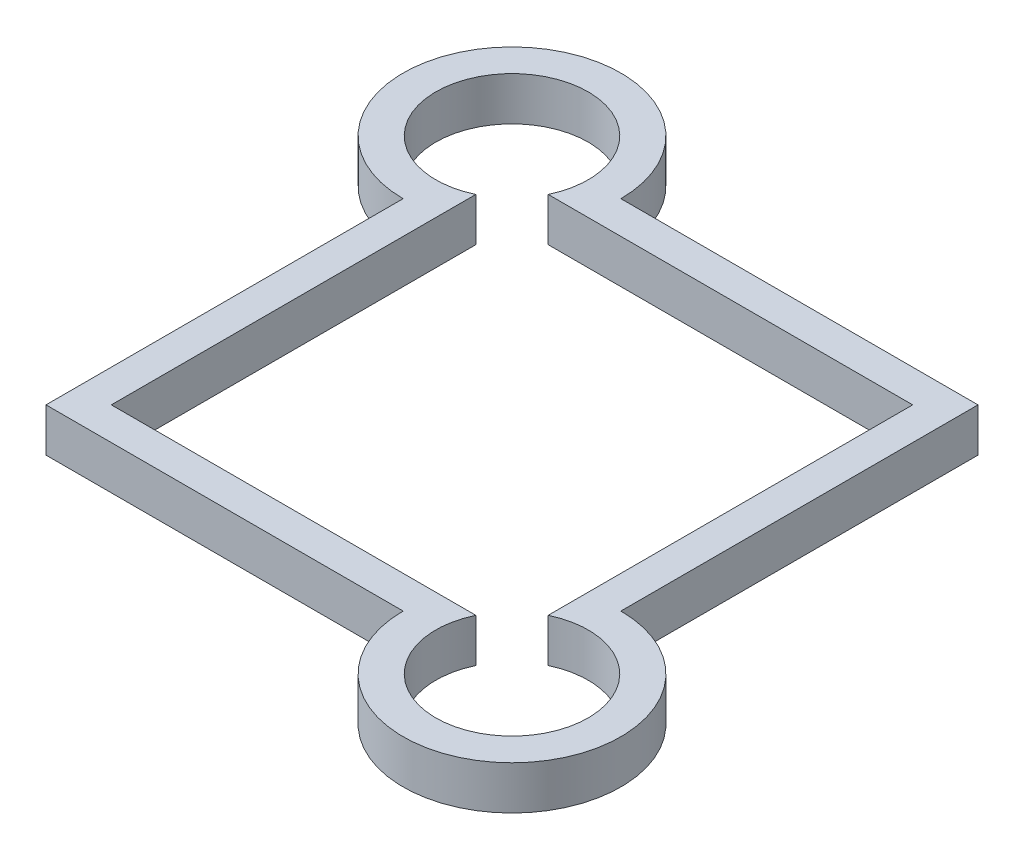
SolidWorks part; units mm, degrees
ref_plane "Ön Düzlem" through (0, 0, 0) normal (0, 0, 1) x (1, 0, 0)
ref_plane "Üst Düzlem" through (0, 0, 0) normal (0, 1, 0) x (1, 0, 0)
ref_plane "Sağ Düzlem" through (0, 0, 0) normal (1, 0, 0) x (0, 0, -1)
sketch "Çizim1" plane through (0, 0, 0) normal (0, 1, 0) x (1, 0, 0)
  line L0 (-66.2238, 67.3805) -> (101.1534, 67.3805)
  line L1 (-47.8466, 82.3805) -> (116.1534, 82.3805)
  line L2 (-97.8466, 32.3805) -> (-97.8466, -131.6195)
  line L3 (-97.8466, -131.6195) -> (66.1534, -131.6195)
  line L4 (116.1534, 82.3805) -> (116.1534, -81.6195)
  line L5 (-82.8466, 50.7578) -> (-82.8466, -116.6195)
  line L6 (-82.8466, -116.6195) -> (84.5306, -116.6195)
  line L7 (101.1534, 67.3805) -> (101.1534, -99.9967)
  line L8 (-97.8466, 117.3805) -> (-97.8466, 123.0819) construction
  line L9 (151.1534, -131.6195) -> (156.8547, -131.6195) construction
  line L10 (116.1534, 82.3805) -> (-97.8466, -131.6195) construction
  line L11 (116.1534, -166.6195) -> (116.1534, -174.9485) construction
  line L13 (-132.8466, 82.3805) -> (-141.1757, 82.3805) construction
  arc A0 (-66.2238, 67.3805) -> (-82.8466, 50.7578) centre (-97.8466, 82.3805) ccw
  arc A1 (-47.8466, 82.3805) -> (-97.8466, 32.3805) centre (-97.8466, 82.3805) ccw
  arc A2 (116.1534, -81.6195) -> (66.1534, -131.6195) centre (116.1534, -131.6195) cw
  arc A3 (101.1534, -99.9967) -> (84.5306, -116.6195) centre (116.1534, -131.6195) cw
  dimension "D7" = 70
  dimension "D8" = 100
  dimension "D1" = 214
  dimension "D2" = 214
  dimension "D3" = 15
  dimension "D4" = 15
  dimension "D5" = 15
  dimension "D6" = 15
extrude "Yükseklik-Ekstrüzyon1" add sketch "Çizim1" along normal blind 20
